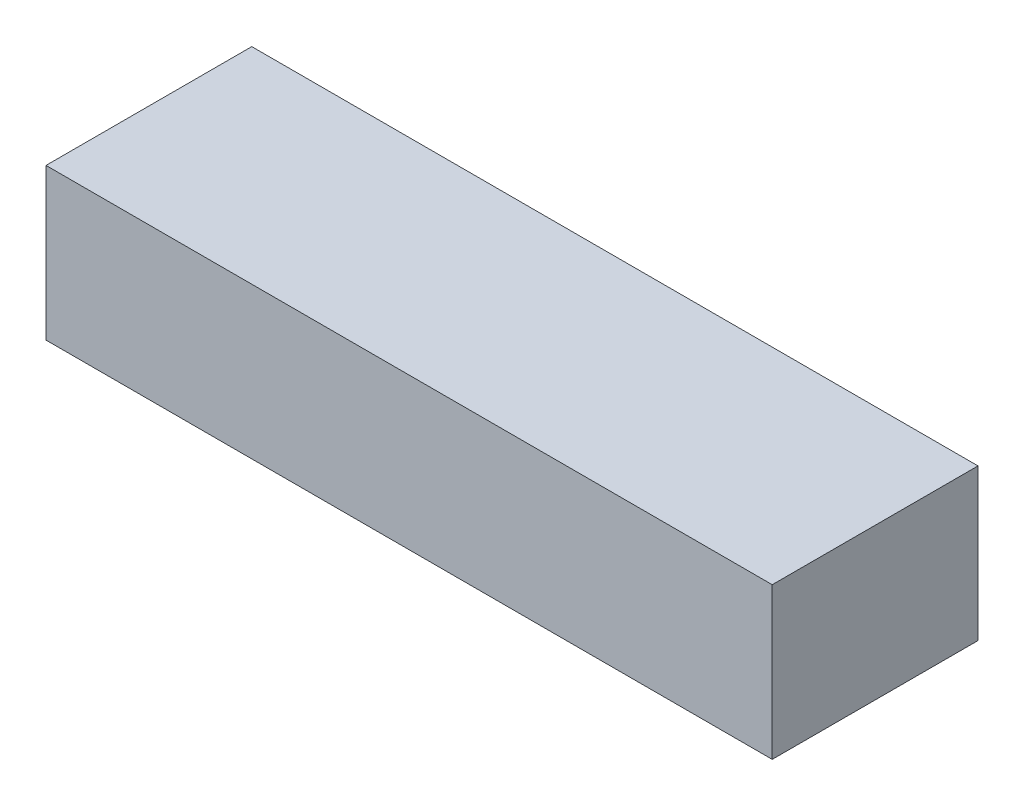
SolidWorks part; units mm, degrees
ref_plane "Front Plane" through (0, 0, 0) normal (0, 0, 1) x (1, 0, 0)
ref_plane "Top Plane" through (0, 0, 0) normal (0, 1, 0) x (1, 0, 0)
ref_plane "Right Plane" through (0, 0, 0) normal (1, 0, 0) x (0, 0, -1)
sketch "Sketch1" plane through (0, 0, 0) normal (0, 1, 0) x (1, 0, 0)
  line L1 (-60, -17) -> (60, -17)
  line L2 (-60, -17) -> (-60, 17)
  line L3 (-60, 17) -> (60, 17)
  line L4 (60, -17) -> (60, 17)
  line L5 (-60, -17) -> (60, 17) construction
  line L6 (-60, 17) -> (60, -17) construction
  point P0 (0, 0)
  dimension "D1" = 120
  dimension "D2" = 34
extrude "Boss-Extrude1" add sketch "Sketch1" along normal blind 25
sketch "Sketch2" plane through (-60, 0, 0) normal (-1, 0, 0) x (0, 0, 1)
  line L1 (8.2805, 10.8411) -> (5.6088, 18.7605)
  line L2 (5.6088, 18.7605) -> (-2.5855, 20.4063)
  line L3 (-2.5855, 20.4063) -> (-8.108, 14.1328)
  line L4 (-8.108, 14.1328) -> (-5.4362, 6.2135)
  line L5 (-5.4362, 6.2135) -> (2.7581, 4.5676)
  line L6 (2.7581, 4.5676) -> (8.2805, 10.8411)
  circle A0 centre (0.0863, 12.487) radius 7.2382 construction
extrude "Boss-Extrude2" add sketch "Sketch2" along normal blind 2 contours L1 L2 L3 L4 L5 L6
